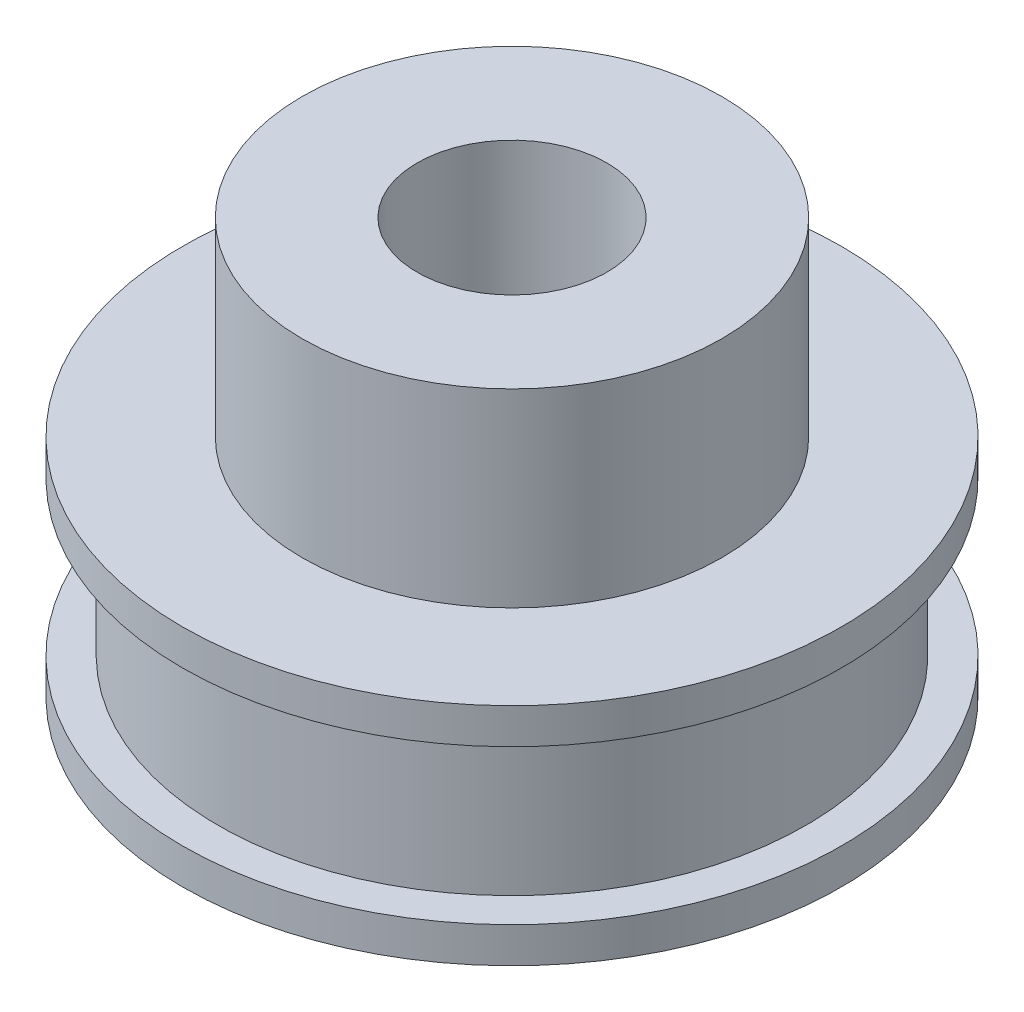
SolidWorks part; units mm, degrees
ref_plane "Face" through (0, 0, 0) normal (0, 0, 1) x (1, 0, 0)
ref_plane "Dessus" through (0, 0, 0) normal (0, 1, 0) x (1, 0, 0)
ref_plane "Droite" through (0, 0, 0) normal (1, 0, 0) x (0, 0, -1)
sketch "Esquisse1" plane through (0, 0, 0) normal (0, 0, 1) x (1, 0, 0)
  line L0 (0, 0) -> (0, 9.7978) construction
  line L1 (4, 0) -> (13.9, 0)
  line L2 (13.9, 0) -> (13.9, 1.5)
  line L3 (13.9, 1.5) -> (12.4, 1.5)
  line L4 (12.4, 1.5) -> (12.4, 8)
  line L5 (12.4, 8) -> (13.9, 8)
  line L6 (13.9, 8) -> (13.9, 9.5)
  line L7 (13.9, 9.5) -> (8.85, 9.5)
  line L8 (8.85, 9.5) -> (8.85, 17.5)
  line L9 (8.85, 17.5) -> (4, 17.5)
  line L10 (4, 17.5) -> (4, 0)
  dimension "D1" = 27.8
  dimension "D2" = 6.5
  dimension "D3" = 8
  dimension "D4" = 17.7
  dimension "D5" = 17.5
  dimension "D6" = 1.5
  dimension "D7" = 1.5
  dimension "D8" = 1.5
revolve "Révolution1" add sketch "Esquisse1" angle 360 about L0
